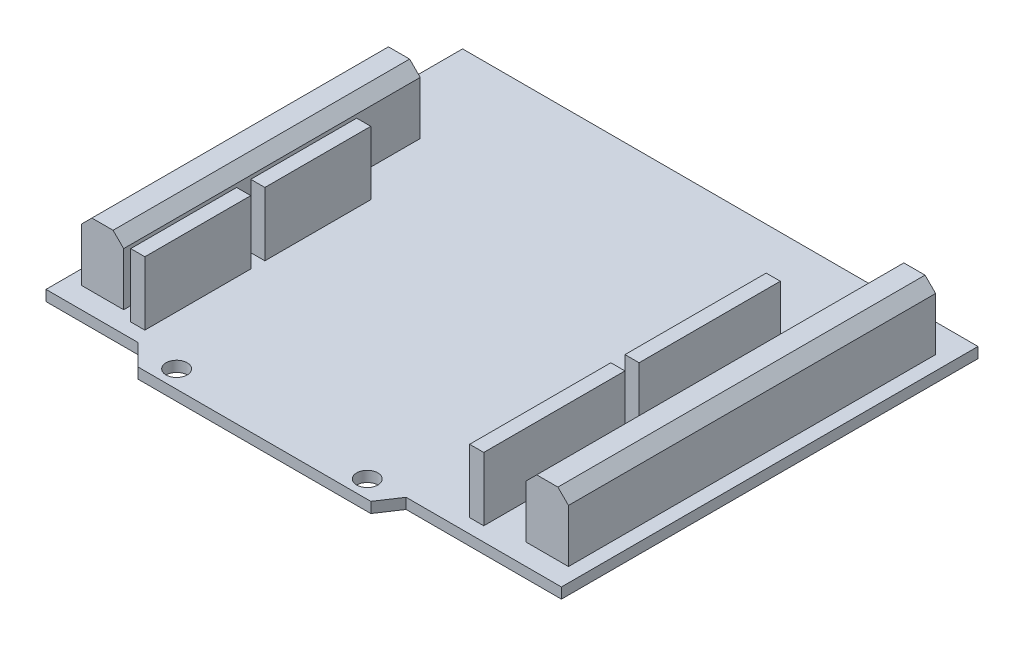
SolidWorks part; units mm, degrees
ref_plane "Front Plane" through (0, 0, 0) normal (0, 0, 1) x (1, 0, 0)
ref_plane "Top Plane" through (0, 0, 0) normal (0, 1, 0) x (1, 0, 0)
ref_plane "Right Plane" through (0, 0, 0) normal (1, 0, 0) x (0, 0, -1)
sketch "Sketch1" plane through (0, 0, 0) normal (0, 1, 0) x (1, 0, 0)
  line L1 (-36.5, -31) -> (36.5, -31)
  line L2 (-36.5, -31) -> (-36.5, 31)
  line L3 (-36.5, 31) -> (36.5, 31)
  line L4 (36.5, -31) -> (36.5, 31)
  line L5 (-36.5, -31) -> (36.5, 31) construction
  line L6 (-36.5, 31) -> (36.5, -31) construction
  point P0 (0, 0)
  dimension "D1" = 62
  dimension "D2" = 73
extrude "Boss-Extrude1" add sketch "Sketch1" along normal mid plane 1.5
sketch "Sketch2" plane through (0, 0.75, 0) normal (0, 1, 0) x (1, 0, 0)
  line L0 (-36.5, -31) -> (-36.5, -28)
  line L1 (-36.5, 31) -> (-36.5, -31) construction
  line L2 (-36.5, -28) -> (-23.5, -28)
  line L3 (-23.5, -28) -> (-20.5, -31)
  line L4 (-36.5, -31) -> (36.5, -31) construction
  line L5 (-20.5, -31) -> (-36.5, -31)
  line L6 (36.5, -31) -> (12.5, -31)
  line L7 (12.5, -31) -> (14.5, -28)
  line L8 (14.5, -28) -> (36.5, -28)
  line L9 (36.5, -31) -> (36.5, 31) construction
  line L10 (36.5, -28) -> (36.5, -31)
  dimension "D1" = 16
  dimension "D2" = 13
  dimension "D3" = 3
  dimension "D4" = 24
  dimension "D5" = 22
  dimension "D6" = 3
extrude "Cut-Extrude1" cut sketch "Sketch2" against normal blind 2
sketch "Sketch3" plane through (0, 0.75, 0) normal (0, 1, 0) x (1, 0, 0)
  line L0 (-36.5, 31) -> (-36.5, -28) construction
  line L1 (-20.5, -31) -> (12.5, -31) construction
  line L2 (-4, -31) -> (-4, -46.078) construction
  line L3 (36.5, -28) -> (14.5, -28) construction
  line L4 (36.5, -28) -> (36.5, 31) construction
  circle A0 centre (-17.5, -28.5) radius 1.5
  circle A1 centre (9.5, -28.5) radius 1.5
  circle A2 centre (24.5, 22) radius 1.5
  dimension "D2" = 3
  dimension "D4" = 3
  dimension "D1" = 19
  dimension "D3" = 2.5
  dimension "D5" = 50
  dimension "D6" = 12
extrude "Cut-Extrude2" cut sketch "Sketch3" against normal blind 2
sketch "Sketch4" plane through (0, 0.75, 0) normal (0, 1, 0) x (1, 0, 0)
  line L0 (-36.5, 31) -> (-36.5, -28) construction
  line L1 (-34.5, 17) -> (-28.5, 17)
  line L2 (-34.5, 17) -> (-34.5, -25)
  line L3 (-34.5, -25) -> (-28.5, -25)
  line L4 (-28.5, 17) -> (-28.5, -25)
  line L5 (-23.5, -28) -> (-36.5, -28) construction
  line L6 (36.5, -28) -> (36.5, 31) construction
  line L7 (34.5, 27) -> (28.5, 27)
  line L8 (34.5, 27) -> (34.5, -25)
  line L9 (34.5, -25) -> (28.5, -25)
  line L10 (28.5, 27) -> (28.5, -25)
  line L11 (36.5, -28) -> (14.5, -28) construction
  line L12 (-24.5, -9) -> (-24.5, 6)
  line L13 (-24.5, -26) -> (-26.5, -26)
  line L14 (-24.5, -26) -> (-24.5, -11)
  line L15 (-24.5, -11) -> (-26.5, -11)
  line L16 (-26.5, -26) -> (-26.5, -11)
  line L17 (-24.5, 6) -> (-26.5, 6)
  line L18 (-26.5, -9) -> (-26.5, 6)
  line L19 (-24.5, -9) -> (-26.5, -9)
  line L20 (21.5, 16) -> (23.5, 16)
  line L21 (21.5, -6) -> (23.5, -6)
  line L22 (21.5, -6) -> (21.5, -26)
  line L23 (21.5, -26) -> (23.5, -26)
  line L24 (23.5, -6) -> (23.5, -26)
  line L25 (21.5, 16) -> (21.5, -4)
  line L26 (21.5, -4) -> (23.5, -4)
  line L27 (23.5, 16) -> (23.5, -4)
  point P6 (-31.5, -25)
  point P29 (25.5, -28)
  point P30 (23.5, -16)
  point P31 (-25.5, -11)
  dimension "D1" = 6
  dimension "D2" = 2
  dimension "D3" = 3
  dimension "D4" = 42
  dimension "D5" = 52
  dimension "D6" = 2
  dimension "D7" = 3
  dimension "D8" = 6
  dimension "D9" = 2
  dimension "D10" = 2
  dimension "D11" = 15
  dimension "D12" = 2
  dimension "D15" = 20
  dimension "D16" = 5
  dimension "D17" = 2
  dimension "D18" = 2
  dimension "D14" = 2
  dimension "D13" = 2
extrude "Boss-Extrude2" add sketch "Sketch4" along normal blind 9
chamfer "Chamfer1" distance 1.5 angle 45 4 edges at (28.5, 9.75, -1) (34.5, 9.75, -1) (-28.5, 9.75, 4) (-34.5, 9.75, 4)
sketch "Sketch5" plane through (0, -0.75, 0) normal (0, -1, 0) x (1, 0, 0)
  line L1 (-24.5, 26) -> (-22.5, 26)
  line L2 (-24.5, 26) -> (-24.5, 11)
  line L3 (-24.5, 11) -> (-22.5, 11)
  line L4 (-22.5, 26) -> (-22.5, 11)
  line L5 (-24.5, 26) -> (-24.5, 11) construction
  line L7 (-24.5, 9) -> (-22.5, 9)
  line L8 (-24.5, 9) -> (-24.5, -6)
  line L9 (-24.5, -6) -> (-22.5, -6)
  line L10 (-22.5, 9) -> (-22.5, -6)
  dimension "D1" = 15
  dimension "D2" = 2
  dimension "D3" = 0
  dimension "D4" = 15
  dimension "D5" = 2
  dimension "D6" = 2
extrude "Boss-Extrude3" add sketch "Sketch5" along normal blind 2
sketch "Sketch6" plane through (0, -0.75, 0) normal (0, -1, 0) x (1, 0, 0)
  line L1 (23.5, 26) -> (25.5, 26)
  line L2 (23.5, 26) -> (23.5, 6)
  line L3 (23.5, 6) -> (25.5, 6)
  line L4 (25.5, 26) -> (25.5, 6)
  line L5 (23.5, 4) -> (25.5, 4)
  line L6 (23.5, 4) -> (23.5, -16)
  line L7 (23.5, -16) -> (25.5, -16)
  line L8 (25.5, 4) -> (25.5, -16)
  dimension "D1" = 20
  dimension "D2" = 20
  dimension "D3" = 2
  dimension "D4" = 2
extrude "Boss-Extrude4" add sketch "Sketch6" along normal blind 2
